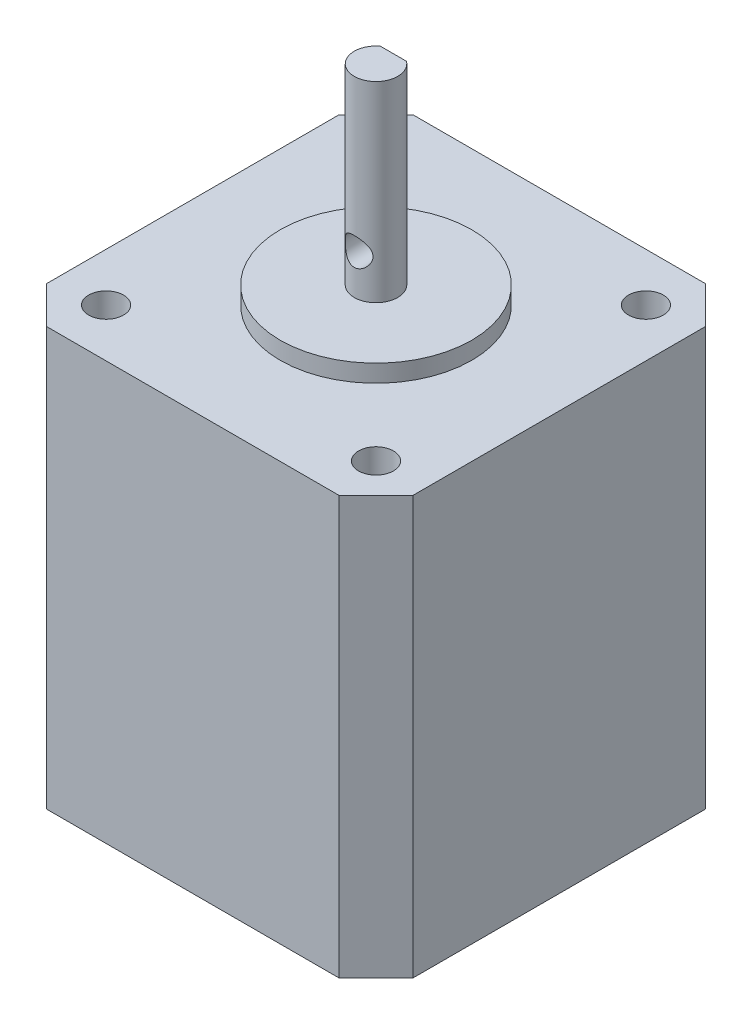
SolidWorks part; units mm, degrees
material "Dual shaft stepper motor"
ref_plane "Front Plane" through (0, 0, 0) normal (0, 0, 1) x (1, 0, 0)
ref_plane "Top Plane" through (0, 0, 0) normal (0, 1, 0) x (1, 0, 0)
ref_plane "Right Plane" through (0, 0, 0) normal (1, 0, 0) x (0, 0, -1)
sketch "Sketch1" plane through (0, 0, 0) normal (0, 1, 0) x (1, 0, 0)
  line L0 (16.8074, -21.05) -> (21.05, -16.8074)
  line L1 (-16.8074, 21.05) -> (16.8074, 21.05)
  line L2 (-21.05, 16.8074) -> (-21.05, -16.8074)
  line L3 (-16.8074, -21.05) -> (16.8074, -21.05)
  line L4 (21.05, 16.8074) -> (21.05, -16.8074)
  line L5 (-18.9287, 18.9287) -> (18.9287, -18.9287) construction
  line L6 (-18.9287, -18.9287) -> (18.9287, 18.9287) construction
  line L7 (0, 0) -> (0, -21.05) construction
  line L8 (0, 0) -> (-21.05, 0) construction
  line L9 (-16.8074, -21.05) -> (-21.05, -16.8074)
  line L10 (-16.8074, 21.05) -> (-21.05, 16.8074)
  line L11 (16.8074, 21.05) -> (21.05, 16.8074)
  dimension "D1" = 6
  dimension "D2" = 21.05
  dimension "D3" = 21.05
extrude "Boss-Extrude1" add sketch "Sketch1" along normal blind 48 contours L1 L11 L4 L0 L3 L9 L2 L10
sketch "Sketch2" plane through (0, 48, 0) normal (0, 1, 0) x (1, 0, 0)
  line L0 (0, 0) -> (0, 21.05) construction
  line L1 (-16.8074, 21.05) -> (16.8074, 21.05) construction
  line L2 (0, 0) -> (21.05, 0) construction
  line L3 (21.05, 16.8074) -> (21.05, -16.8074) construction
  circle A0 centre (-15.5, 15.5) radius 2
  circle A1 centre (15.5, 15.5) radius 2
  circle A2 centre (15.5, -15.5) radius 2
  circle A3 centre (-15.5, -15.5) radius 2
  dimension "D1" = 4
  dimension "D2" = 15.5
  dimension "D3" = 15.5
extrude "Cut-Extrude1" cut sketch "Sketch2" against normal up to surface (48 mm away) up to face at (0, 0, 0)
sketch "Sketch3" plane through (0, 48, 0) normal (0, 1, 0) x (1, 0, 0)
  circle A0 centre (0, 0) radius 11
  dimension "D1" = 22
extrude "Boss-Extrude2" add sketch "Sketch3" along normal blind 2
sketch "Sketch4" plane through (0, 50, 0) normal (0, 1, 0) x (1, 0, 0)
  circle A0 centre (0, 0) radius 2.5
  dimension "D1" = 5
extrude "Boss-Extrude3" add sketch "Sketch4" along normal blind 22
sketch "Sketch5" plane through (0, 72, 0) normal (0, 1, 0) x (1, 0, 0)
  line L0 (-1.5, 2) -> (1.5, 2)
  circle A0 centre (0, 0) radius 2.5 construction
  arc A1 (1.5, 2) -> (-1.5, 2) centre (0, 0) ccw
  point P4 (0, -2.5)
  dimension "D1" = 4.5
extrude "Cut-Extrude2" cut sketch "Sketch5" against normal blind 15
ref_plane "Plane1" through (0, 0, -2.5) normal (0, 0, -1) x (-1, 0, 0)
sketch "Sketch6" plane through (0, 0, -2.5) normal (0, 0, -1) x (-1, 0, 0)
  line L0 (2.5, 50) -> (-2.5, 50) construction
  line L1 (1.5, 57) -> (-1.5, 57) construction
  line L2 (2.5, 50) -> (-2.5, 50) construction
  line L3 (1.5, 57) -> (-1.5, 57) construction
  line L8 (0, 50) -> (0, 72) construction
  line L9 (2.5, 72) -> (-2.5, 72) construction
  line L10 (1.5, 57) -> (2.5, 57) construction
  circle A0 centre (0, 54.5875) radius 1.5875
  point P5 (0, 56.175)
  point P13 (0, 53)
  dimension "D1" = 3.175
  dimension "D2" = 3
extrude "Cut-Extrude5" cut sketch "Sketch6" against normal through all
sketch "Sketch7" plane through (0, 0, 0) normal (0, -1, 0) x (1, 0, 0)
  circle A0 centre (0, 0) radius 2.5
  dimension "D1" = 5
extrude "Boss-Extrude4" add sketch "Sketch7" along normal blind 10
sketch "Sketch8" plane through (0, -10, 0) normal (0, -1, 0) x (1, 0, 0)
  circle A0 centre (0, 0) radius 0.75
  dimension "D1" = 1.5
extrude "Cut-Extrude6" cut sketch "Sketch8" against normal up to surface (10 mm away) up to face at (0, 0, -2.5)
